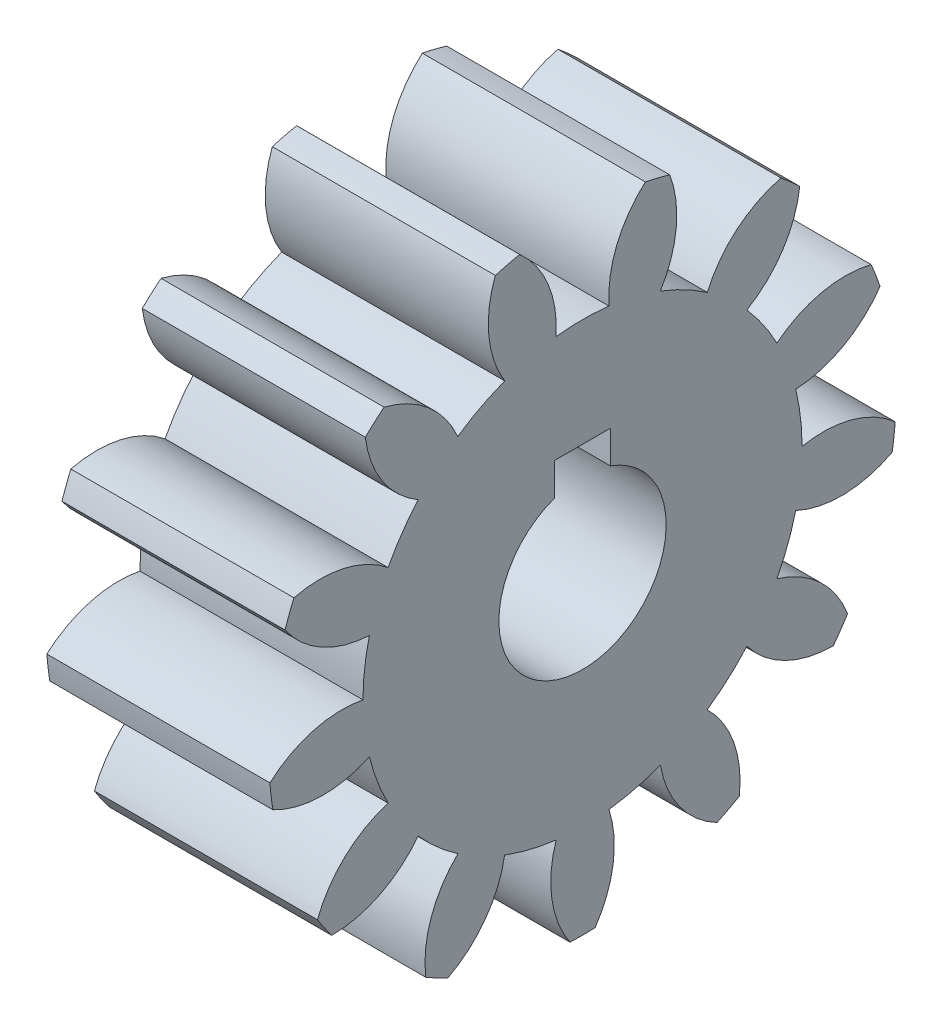
SolidWorks part; units mm, degrees
ref_plane "Plane1" through (0, 0, 0) normal (0, 0, 1) x (1, 0, 0)
ref_plane "Plane2" through (0, 0, 0) normal (0, 1, 0) x (1, 0, 0)
ref_plane "Plane3" through (0, 0, 0) normal (1, 0, 0) x (0, 0, -1)
sketch "HoldingSke" plane through (0, 0, 0) normal (0, 1, 0) x (1, 0, 0)
  line L0 (0, 0) -> (0.6496, -0.15)
  line L1 (-15, 0) -> (100, 0) construction
  line L2 (0, 0) -> (-2.1039, 2.3779)
  line L3 (0, 0) -> (-11.863, 4.5341)
  line L4 (0, 0) -> (8.4147, 1.9427)
  line L5 (0, 0) -> (-46.8476, -17.4728)
  line L6 (0, 0) -> (-6.6317, -4.4744)
  line L7 (-2.1039, 2.3779) -> (8.6586, 51.2059)
  line L8 (-76.2, 54.61) -> (-75.2, 54.61)
  line L9 (-67.7845, 28.3722) -> (-49.3413, 33.142)
  line L10 (-76.2, 71.12) -> (104.1128, 71.12)
  line L11 (0, 0) -> (-8, 0)
  line L12 (-76.2, 101.6) -> (-76.147, 101.6)
  line L13 (24.9733, 27.94) -> (52.9518, 28.4284)
  line L14 (24.9733, 27.94) -> (24.9743, 27.94)
  line L15 (24.9733, 27.94) -> (100.4006, 29.5858)
  line L16 (-63.627, -1.5) -> (-12.827, -1.5)
  circle A0 centre (0, 0) radius 3
  circle A1 centre (0, 0) radius 7.874
  circle A2 centre (0, 0) radius 37.5
  circle A3 centre (0, 0) radius 3
  dimension "MHD" = 15.748
  dimension "Hub_dia" = 75
  dimension "Bore" = 6
  dimension "MBD" = 6
  dimension "Num_teeth" = 13
  dimension "Pitch" = 0.6667
  dimension "Overall_len" = 50
  dimension "Show_teeth" = 13
  dimension "Thickness" = 8
  dimension "OAL" = 50.0001
  dimension "T_dim" = 1
  dimension "Ap" = 14.5
  dimension "H" = 19.05
  dimension "Pitch_radius" = 180.3128
  dimension "Width" = 8
  dimension "Backlash" = 0.053
  dimension "Addendum_fac" = 1
  dimension "Dedendum_fac" = 1.25
  dimension "Clearance_fac" = 0.25
  dimension "Dedendum_add" = 0.001
  dimension "Module" = 1.5
sketch "BasProSke" plane through (0, 0, 0) normal (0, 1, 0) x (1, 0, 0)
  line L0 (-10, 0) -> (60, 0) construction
  line L1 (0, 0) -> (0, 11.25)
  line L2 (0, 0) -> (8, 0)
  line L3 (8, 0) -> (8, 11.25)
  line L4 (8, 11.25) -> (0, 11.25)
  dimension "Thickness" = 8
  dimension "Diameter" = 22.5
revolve "Base-Revolve" add sketch "BasProSke" angle 360 about L0
sketch "TooCutSke" plane through (0, 0, 0) normal (1, 0, 0) x (0, 0, -1)
  line L1 (0, 0) -> (0, 107) construction
  line L2 (0, 0) -> (-1.2679, 9.6672) construction
  line L3 (0, 0) -> (-4.6378, 18.8163) construction
  line L4 (-1.2679, 9.6672) -> (-2.3189, 9.4082) construction
  arc A0 (0.9514, 7.8163) -> (-0.9514, 7.8163) centre (0, 0) ccw
  arc A1 (2.2774, 11.043) -> (-2.2774, 11.043) centre (0, 0) ccw
  circle A2 centre (0, 0) radius 9.75 construction
  circle A3 centre (0, 0) radius 9.4394 construction
  arc A4 (-0.9514, 7.8163) -> (-2.2774, 11.043) centre (-4.8408, 8.1037) ccw
  arc A5 (2.2774, 11.043) -> (0.9514, 7.8163) centre (4.8408, 8.1037) ccw
  dimension "Root_dia" = 15.748
  dimension "Overcut_dia" = 22.5508
  dimension "Pitch_dia" = 19.5
  dimension "Base_dia" = 18.8789
  dimension "Flank_rad" = 3.9
  dimension "Half_ang" = 13.846
  dimension "Half_CT" = 1.0825
extrude "ToothCut" cut sketch "TooCutSke" along normal through all
fillet "Breaks" [suppressed] radius 0.03
fillet "RootFillets" [suppressed] radius 0.376
pattern_circular "TeethCuts" count 13 every 27.692 about axis through (-10, 0, 0) along (1, 0, 0) of "ToothCut", "RootFillets", "Breaks"
sketch "HubNeaOneSke" plane through (0, 0, 0) normal (-1, 0, 0) x (0, 0, 1)
  circle A0 centre (0, 0) radius 7.874
  dimension "Diameter" = 15.748
extrude "HubNearOne" [suppressed] add sketch "HubNeaOneSke" along normal blind 42.0001
sketch "HubNeaBotSke" plane through (0, 0, 0) normal (-1, 0, 0) x (0, 0, 1)
  circle A0 centre (0, 0) radius 7.874
  dimension "Diameter" = 15.748
extrude "HubNearBoth" [suppressed] add sketch "HubNeaBotSke" along normal blind 21
ref_plane "FarPln" through (8, 0, 0) normal (1, 0, 0) x (0, 0, -1)
sketch "HubFarSke" plane through (8, 0, 0) normal (1, 0, 0) x (0, 0, -1)
  circle A0 centre (0, 0) radius 7.874
  dimension "Diameter" = 15.748
extrude "HubFar" [suppressed] add sketch "HubFarSke" along normal blind 21
sketch "BorSke" plane through (0, 0, 0) normal (1, 0, 0) x (0, 0, -1)
  circle A0 centre (0, 0) radius 3
  dimension "Diameter" = 6
extrude "Bore" cut sketch "BorSke" along normal mid plane 100.0001
sketch "KeySke" plane through (0, 0, 0) normal (1, 0, 0) x (0, 0, -1)
  line L0 (-1, 0) -> (-1, 4)
  line L1 (-1, 4) -> (1, 4)
  line L2 (1, 4) -> (1, 0)
  line L3 (0, 0) -> (0, 34) construction
  line L4 (-1, 0) -> (1, 0)
  dimension "Offset" = 4
  dimension "Width" = 2
extrude "Keyway" cut sketch "KeySke" along normal mid plane 100.0001
pattern_circular "Keyway2" [suppressed] count 2 every 90 about axis through (-10, 0, 0) along (1, 0, 0)
equation "' \"Module@HoldingSke\" = 6.35"
equation "' \"Num_teeth@HoldingSke\" = 12"
equation "' \"Ap@HoldingSke\" =  20"
equation "' \"Ap@HoldingSke\" = 20"
equation "' \"Width@HoldingSke\" = 0.5 * 25.4"
equation "' \"Hub_dia@HoldingSke\"= 1 * 25.4"
equation "' \"Hub_dia@HoldingSke\" = 1 * 25.4"
equation "' \"Overall_len@HoldingSke\" = 1.0 * 25.4"
equation "' \"Bore@HoldingSke\" = 0.75 * 25.4"
equation "' \"T_dim@HoldingSke\" = 0.1 * 25.4"
equation "' \"Width@KeySke\" = 0.25 * 25.4"
equation "' \"Show_teeth@HoldingSke\" = 13"
equation "' \"Backlash@HoldingSke\" = 0.009 * 25.4"
equation "' \"Addendum_fac@HoldingSke\" = 1.0"
equation "' \"Dedendum_fac@HoldingSke\" = 1.25"
equation "' \"Dedendum_add@HoldingSke\" = 0.00005 * 25.4"
equation "' \"Clearance_fac@HoldingSke\" = 0.25"
equation "\"Pitch@HoldingSke\" = 1 / \"Module@HoldingSke\""
equation "\"Overcut_dia@TooCutSke\" = (\"Num_teeth@HoldingSke\" + 2 * \"Addendum_fac@HoldingSke\") / \"Pitch@HoldingSke\" + 0.002 * 25.4"
equation "\"Pitch_dia@TooCutSke\" = \"Num_teeth@HoldingSke\" / \"Pitch@HoldingSke\""
equation "\"Base_dia@TooCutSke\" = \"Num_teeth@HoldingSke\" / \"Pitch@HoldingSke\" * cos((\"Ap@HoldingSke\"  * 3.14159265 / 180))"
equation "\"Root_dia@TooCutSke\" = (\"Num_teeth@HoldingSke\" + 2) / \"Pitch@HoldingSke\" - 2 * (\"Addendum_fac@HoldingSke\" + \"Dedendum_fac@HoldingSke\") / \"Pitch@HoldingSke\" - \"Dedendum_add@HoldingSke\" * 2"
equation "\"Half_ang@TooCutSke\" = 180 / \"Num_teeth@HoldingSke\""
equation "\"Half_CT@TooCutSke\" = \"Num_teeth@HoldingSke\" / \"Pitch@HoldingSke\" * sin((3.14159265 / 2 / \"Num_teeth@HoldingSke\")) / 2 - 7 * \"Backlash@HoldingSke\" / 4"
equation "\"Flank_rad@TooCutSke\" = \"Num_teeth@HoldingSke\" / \"Pitch@HoldingSke\" / 5"
equation "\"Radius@RootFillets\" = \"Clearance_fac@HoldingSke\" / \"Pitch@HoldingSke\" + \"Dedendum_add@HoldingSke\""
equation "\"Break_rad@Breaks\" = 0.02 / \"Pitch@HoldingSke\""
equation "\"Thickness@HoldingSke\" = \"Width@HoldingSke\""
equation "\"OAL@HoldingSke\" = \"Thickness@HoldingSke\""
equation "\"MHD@HoldingSke\" = (\"Num_teeth@HoldingSke\" + 2) / \"Pitch@HoldingSke\" - 2 * (\"Addendum_fac@HoldingSke\" + \"Dedendum_fac@HoldingSke\")  / \"Pitch@HoldingSke\" - \"Dedendum_add@HoldingSke\" * 2"
equation "\"MBD@HoldingSke\" = (\"Num_teeth@HoldingSke\" + 2) / \"Pitch@HoldingSke\" - 2 * (\"Addendum_fac@HoldingSke\" + \"Dedendum_fac@HoldingSke\")  / \"Pitch@HoldingSke\" - \"Dedendum_add@HoldingSke\" * 2 - 0.002 * 25.4"
equation "\"MHD@HoldingSke\" = ((sgn( \"MHD@HoldingSke\" - \"Hub_dia@HoldingSke\" )-1)*( \"MHD@HoldingSke\" - \"Hub_dia@HoldingSke\" ))/-2+ \"Hub_dia@HoldingSke\""
equation "\"MBD@HoldingSke\" = ((sgn( \"MBD@HoldingSke\" - \"Bore@HoldingSke\" )-1)*( \"MBD@HoldingSke\" - \"Bore@HoldingSke\" ))/-2+ \"Bore@HoldingSke\""
equation "\"OAL@HoldingSke\" = ((sgn( \"OAL@HoldingSke\" - \"Overall_len@HoldingSke\" )+1)*( \"OAL@HoldingSke\" - \"Overall_len@HoldingSke\" ))/2 + \"Overall_len@HoldingSke\" + 0.000002 * 25.4"
equation "\"Num_teeth@TeethCuts\" = int( \"Show_teeth@HoldingSke\" ) + 1"
equation "\"Num_teeth@TeethCuts\" = ((sgn( \"Num_teeth@TeethCuts\" - \"Num_teeth@HoldingSke\" )-1)*( \"Num_teeth@TeethCuts\" - \"Num_teeth@HoldingSke\" ))/-2+ \"Num_teeth@HoldingSke\""
equation "\"Num_teeth@TeethCuts\" = ((sgn( \"Num_teeth@TeethCuts\" - 2.0)+1)*( \"Num_teeth@TeethCuts\" - 2.0))/2 +2.0"
equation "\"Angle@TeethCuts\" = 360.0 / \"Num_teeth@HoldingSke\""
equation "\"Diameter@BasProSke\" = (\"Num_teeth@HoldingSke\" + 2 * \"Addendum_fac@HoldingSke\") / \"Pitch@HoldingSke\""
equation "\"Thickness@BasProSke\"  = \"Thickness@HoldingSke\""
equation "' \"Fillet_rad@BasProSke\" =  \"Thickness@HoldingSke\" * 0.05"
equation "' \"Fillet_rad@BasProSke\" = \"Thickness@HoldingSke\" * 0.05"
equation "\"MHD@HoldingSke\" = ((sgn( \"MHD@HoldingSke\" - \"Root_dia@TooCutSke\" )-1)*( \"MHD@HoldingSke\" - \"Root_dia@TooCutSke\" ))/-2+ \"Root_dia@TooCutSke\""
equation "\"Diameter@HubNeaOneSke\" = \"MHD@HoldingSke\""
equation "\"Length@HubNearOne\" = \"OAL@HoldingSke\" - \"Thickness@BasProSke\""
equation "\"Diameter@HubNeaBotSke\" = \"MHD@HoldingSke\""
equation "\"Length@HubNearBoth\" = ( \"OAL@HoldingSke\" - \"Thickness@BasProSke\" ) / 2.0"
equation "\"Thickness@FarPln\" = \"Thickness@BasProSke\""
equation "\"Diameter@HubFarSke\" = \"MHD@HoldingSke\""
equation "\"Length@HubFar\" = ( \"OAL@HoldingSke\" - \"Thickness@BasProSke\" ) / 2.0"
equation "\"Diameter@BorSke\" = \"MBD@HoldingSke\""
equation "\"D1@Bore\" = \"OAL@HoldingSke\" * 2.0"
equation "\"D1@Keyway\" = \"OAL@HoldingSke\" * 2.0"
equation "\"Offset@KeySke\" = \"T_dim@HoldingSke\" + \"MBD@HoldingSke\" / 2.0"
